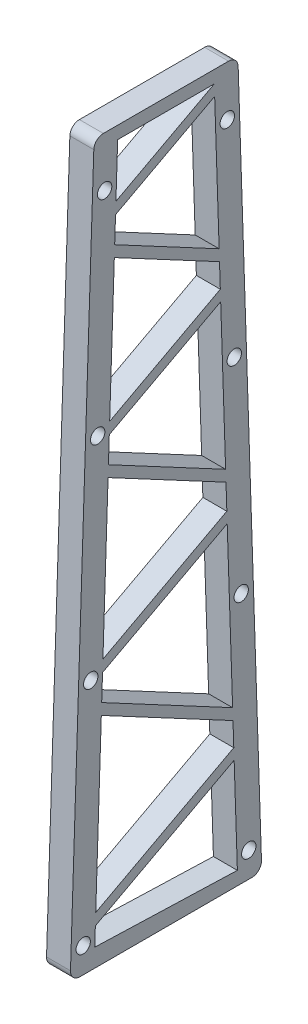
SolidWorks part; units mm, degrees
ref_plane "Front Plane" through (0, 0, 0) normal (0, 0, 1) x (1, 0, 0)
ref_plane "Top Plane" through (0, 0, 0) normal (0, 1, 0) x (1, 0, 0)
ref_plane "Right Plane" through (0, 0, 0) normal (1, 0, 0) x (0, 0, -1)
sketch "Sketch1" plane through (0, 0, 0) normal (0, 1, 0) x (1, 0, 0)
  line L1 (0, 0) -> (5, 0)
  line L2 (0, 0) -> (0, -40)
  line L3 (0, -40) -> (5, -40)
  line L4 (5, 0) -> (5, -40)
ref_plane "Plane1" through (0, 0, 0) normal (0, 1, 0) x (1, 0, 0)
ref_plane "Plane2" through (0, 150, 0) normal (0, 1, 0) x (1, 0, 0)
sketch "Sketch3" plane through (0, 150, 0) normal (0, 1, 0) x (1, 0, 0)
  line L0 (0, 0) -> (0, -40) construction
  line L1 (0, -5) -> (5, -5)
  line L2 (0, -5) -> (0, -35)
  line L3 (0, -35) -> (5, -35)
  line L4 (5, -5) -> (5, -35)
  line L5 (5, 0) -> (5, -40) construction
loft "Loft5" add profiles "Sketch3", "Sketch1"
sketch "Sketch4" plane through (5, 0, 0) normal (1, 0, 0) x (0, 0, -1)
  line L0 (-5, 150) -> (0, 0) construction
  line L4 (-9.8391, 145.0883) -> (-8.905, 117.0662)
  line L5 (-30.0847, 147.3765) -> (-30.45, 136.4162)
  line L6 (-9.9153, 147.3765) -> (-30.45, 136.4162)
  line L8 (-30.5291, 134.0451) -> (-9.8391, 145.0883)
  line L9 (-30.5291, 134.0451) -> (-30.7071, 128.703)
  line L10 (-30.7071, 128.703) -> (-8.905, 117.0662)
  line L11 (-8.826, 114.6952) -> (-30.7834, 126.4149)
  line L12 (-34.744, 7.5963) -> (-34.8706, 3.7982)
  line L13 (-5.7715, 23.0603) -> (-5.0963, 2.8057)
  line L14 (-30.7834, 126.4149) -> (-31.7539, 97.2987)
  line L15 (-33.2425, 52.6412) -> (-33.4206, 47.2991)
  line L16 (-7.2205, 66.5303) -> (-6.0932, 32.7132)
  line L17 (-31.833, 94.9276) -> (-8.5807, 107.3384)
  line L18 (-8.657, 109.6266) -> (-31.7539, 97.2987)
  line L19 (-33.4969, 45.0109) -> (-34.665, 9.9674)
  line L20 (-31.1802, 95.2761) -> (-31.833, 94.9276)
  line L21 (-31.833, 94.9276) -> (-32.011, 89.5855)
  line L22 (-31.1802, 89.1421) -> (-32.011, 89.5855)
  line L23 (-6.0142, 30.3422) -> (-5.8477, 25.3484)
  line L24 (-7.4748, 74.1606) -> (-32.0873, 87.2974)
  line L25 (-32.011, 89.5855) -> (-7.5538, 76.5316)
  line L26 (-9.2065, 77.4137) -> (-7.5538, 76.5316)
  line L27 (-9.2065, 75.0849) -> (-7.4748, 74.1606)
  line L28 (-7.4748, 74.1606) -> (-7.2967, 68.8185)
  line L29 (-9.2065, 67.7991) -> (-7.2967, 68.8185)
  line L30 (-9.2065, 65.4703) -> (-7.2205, 66.5303)
  line L31 (-33.2425, 52.6412) -> (-7.2205, 66.5303)
  line L32 (-7.2967, 68.8185) -> (-33.1635, 55.0122)
  line L33 (-30.8025, 56.2724) -> (-33.1635, 55.0122)
  line L34 (-28.8332, 54.9946) -> (-33.2425, 52.6412)
  line L35 (-32.0873, 87.2974) -> (-33.1635, 55.0122)
  line L36 (-6.0142, 30.3422) -> (-33.4969, 45.0109)
  line L37 (-30.8025, 43.5728) -> (-33.4969, 45.0109)
  line L38 (-28.8332, 44.8506) -> (-33.4206, 47.2991)
  line L39 (-33.4206, 47.2991) -> (-6.0932, 32.7132)
  line L40 (-10.0028, 34.7999) -> (-6.0932, 32.7132)
  line L41 (-8.4107, 31.6213) -> (-6.0142, 30.3422)
  line L42 (-8.5807, 107.3384) -> (-7.5538, 76.5316)
  line L43 (-28.8332, 10.7512) -> (-34.744, 7.5963)
  line L44 (-30.8025, 12.0289) -> (-34.665, 9.9674)
  line L45 (-34.744, 7.5963) -> (-5.7715, 23.0603)
  line L46 (-10.0028, 20.8018) -> (-5.7715, 23.0603)
  line L47 (-8.4107, 23.9804) -> (-5.8477, 25.3484)
  line L48 (-5.8477, 25.3484) -> (-34.665, 9.9674)
  line L49 (-8.826, 114.6952) -> (-8.657, 109.6266)
  line L50 (-34.8706, 3.7982) -> (-5.0963, 2.8057)
  line L51 (-30.0847, 147.3765) -> (-9.9153, 147.3765)
  circle A0 centre (-37.2763, 5.2813) radius 1.5
  circle A1 centre (-35.7042, 52.4466) radius 1.5
  circle A2 centre (-34.2556, 95.9028) radius 1.5
  circle A3 centre (-32.801, 139.5412) radius 1.5
  circle A4 centre (-7.199, 139.5412) radius 1.5
  circle A5 centre (-5.7444, 95.9028) radius 1.5
  circle A6 centre (-4.2958, 52.4466) radius 1.5
  circle A7 centre (-2.7237, 5.2813) radius 1.5
extrude "Cut-Extrude2" cut sketch "Sketch4" against normal blind 10 contours L12 L50 L13 L45 L43 | L48 L47 L23 L36 L19 L44 | L38 L39 L16 L30 L31 L15 | L24 L35 L32 L29 L28 | L42 L17 L21 L22 L25 | L49 L11 L14 L18 | L9 L10 L4 L8 | L51 L5 L6 | A1 | A0 | A7 | A6 | A5 | A2 | A4 | A3
fillet "Fillet1" radius 2 1 edges
fillet "Fillet2" radius 2 1 edges
fillet "Fillet3" radius 2 2 edges
sketch "Sketch5" plane through (5, 0, 0) normal (1, 0, 0) x (0, 0, -1)
  line L1 (-30.4066, 2.5977) -> (-10.4607, 2.5977)
  line L2 (-30.4066, 2.5977) -> (-30.4066, 0.5678)
  line L3 (-30.4066, 0.5678) -> (-10.4607, 0.5678)
  line L4 (-10.4607, 2.5977) -> (-10.4607, 0.5678)
